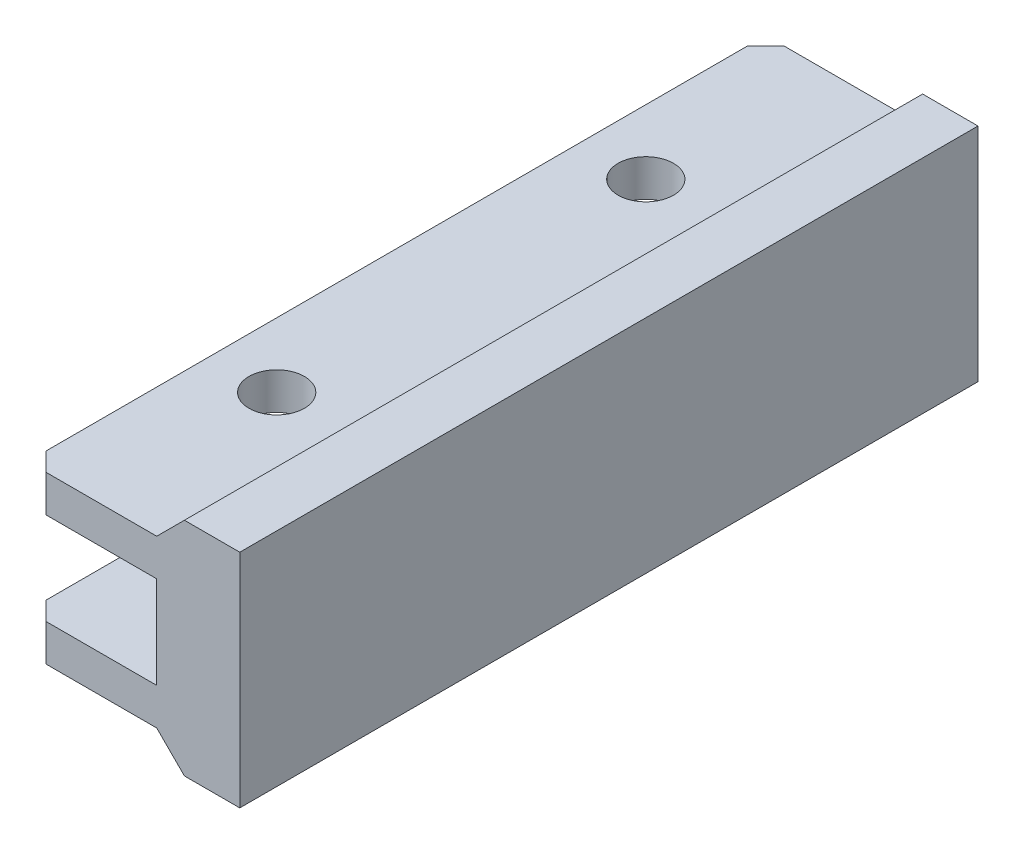
SolidWorks part; units mm, degrees
material "ABS"
ref_plane "Alzado" through (0, 0, 0) normal (1, 0, 0) x (0, 1, 0)
ref_plane "Planta" through (0, 0, 0) normal (0, 0, 1) x (0, 1, 0)
ref_plane "Vista lateral" through (0, 0, 0) normal (0, 1, 0) x (-1, 0, 0)
sketch "Croquis1" plane through (0, 0, 0) normal (0, 0, 1) x (0, 1, 0)
  line L0 (0, 0) -> (0, 11.5) construction
  line L1 (-6, 0) -> (6, 0)
  line L2 (6, 0) -> (6, 3)
  line L3 (6, 3) -> (4.5, 4.5)
  line L4 (4.5, 4.5) -> (4.5, 11.5)
  line L5 (4.5, 11.5) -> (2.5, 11.5)
  line L6 (-2.5, 4.5) -> (2.5, 4.5)
  line L7 (2.5, 4.5) -> (2.5, 11.5)
  line L8 (-6, 0) -> (-6, 3)
  line L9 (-6, 3) -> (-4.5, 4.5)
  line L10 (-4.5, 4.5) -> (-4.5, 11.5)
  line L11 (-4.5, 11.5) -> (-2.5, 11.5)
  line L12 (-2.5, 4.5) -> (-2.5, 11.5)
  point P16 (0, 4.5)
  dimension "D1" = 4.5
  dimension "D2" = 11.5
  dimension "D3" = 2.5
  dimension "D4" = 6
  dimension "D5" = 2
  dimension "D6" = 45
extrude "Saliente-Extruir1" add sketch "Croquis1" along normal mid plane 40
sketch "Croquis2" plane through (0, 4.5, 0) normal (0, 1, 0) x (-1, 0, 0)
  line L0 (8, 20) -> (8, -20) construction
  line L1 (4.5, 20) -> (11.5, 20) construction
  line L2 (4.5, -20) -> (11.5, -20) construction
  point P6 (8, 10)
  point P7 (8, -10)
  point P8 (8, 0)
  dimension "D1" = 10
  dimension "D2" = 20
hole_wizard "Taladro de margen para M31" positions "Croquis2" profile "Croquis3" hole size "M3" standard "Ansi Metric" end condition through all
sketch "Croquis3" plane through (-8, 4.5, -10) normal (1, 0, 0) x (0, 0, 1)
  line L0 (0, 0) -> (0, 10.5)
  line L1 (0, 10.5) -> (1.5, 10.5)
  line L2 (1.5, 10.5) -> (1.5, 0)
  line L5 (1.5, 0) -> (0, 0)
  line L11 (0, -6.35) -> (0, 107.95) construction
  dimension "Diámetro de taladro hasta el siguiente" = 3
  dimension "Profundidad de taladro hasta el siguiente" = 10.5
chamfer "Chaflán2" distance 1 angle 45 4 edges at (-11.5, -3.5, -20) (-11.5, 3.5, -20) (-11.5, 3.5, 20) (-11.5, -3.5, 20)
